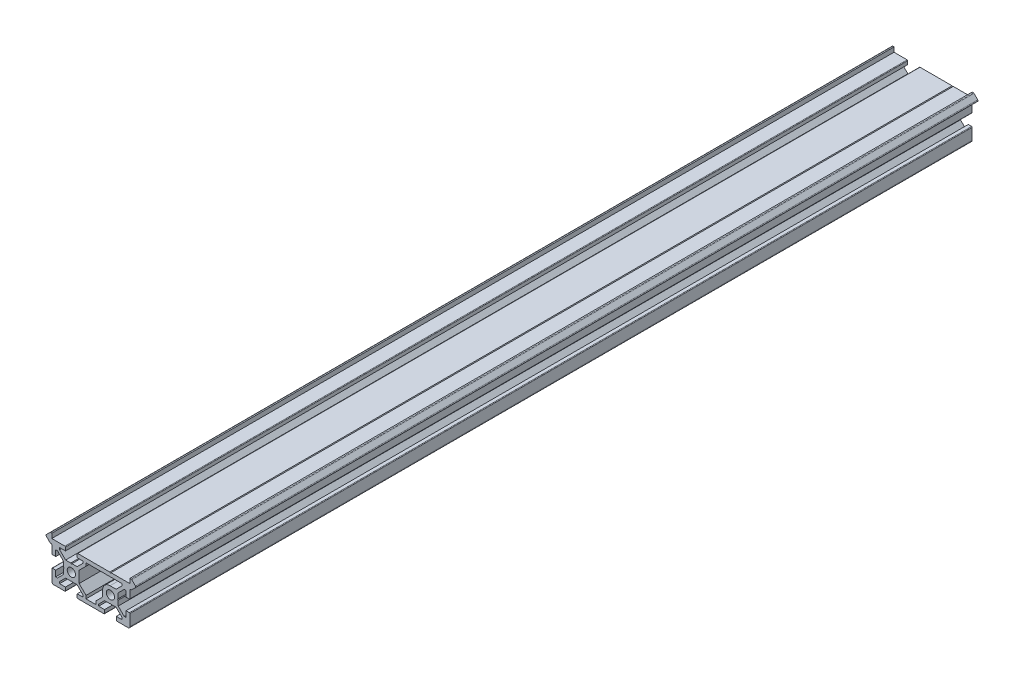
SolidWorks part; units mm, degrees
ref_plane "Front Plane" through (0, 0, 0) normal (0, 0, 1) x (1, 0, 0)
ref_plane "Top Plane" through (0, 0, 0) normal (0, 1, 0) x (1, 0, 0)
ref_plane "Right Plane" through (0, 0, 0) normal (1, 0, 0) x (0, 0, -1)
sketch "Model" plane through (0, 0, 0) normal (0, 0, 1) x (1, 0, 0)
  line L0 (0, 0) -> (0, 76.2) construction
  line L1 (0, 0) -> (101.6, 0) construction
  line L2 (0, 76.2) -> (101.6, 76.2) construction
  line L3 (101.6, 0) -> (101.6, 76.2) construction
  line L4 (28.7715, 48.1056) -> (30.6465, 49.9806)
  line L5 (31.5929, 50.127) -> (31.5929, 47.752)
  line L6 (31.5929, 44.877) -> (31.5929, 41.052)
  line L7 (31.5929, 34.452) -> (31.5929, 28.752)
  line L8 (33.5929, 31.752) -> (33.5929, 34.752)
  line L9 (33.5929, 40.752) -> (33.5929, 43.752)
  line L10 (35.5929, 29.752) -> (35.5929, 30.6914)
  line L11 (35.5929, 44.8127) -> (35.5929, 45.752)
  line L12 (37.5929, 40.6914) -> (37.5929, 38.052)
  line L13 (37.5929, 37.452) -> (37.5929, 34.8127)
  line L14 (38.5929, 28.052) -> (38.5929, 29.752)
  line L15 (38.5929, 45.752) -> (38.5929, 47.452)
  line L16 (32.5929, 27.752) -> (38.2929, 27.752)
  line L17 (44.8929, 27.752) -> (58.2929, 27.752)
  line L18 (64.8929, 27.752) -> (70.5929, 27.752)
  line L19 (37.5929, 38.052) -> (37.8929, 37.752)
  line L20 (41.5929, 34.052) -> (41.8929, 33.752)
  line L21 (30.6465, 45.5235) -> (28.7715, 47.3985)
  line L22 (41.8929, 41.752) -> (41.5929, 41.452)
  line L23 (37.8929, 37.752) -> (37.5929, 37.452)
  line L24 (67.5929, 29.752) -> (64.5929, 29.752)
  line L25 (58.5929, 29.752) -> (55.5929, 29.752)
  line L26 (54.0929, 29.752) -> (49.0929, 29.752)
  line L27 (47.5929, 29.752) -> (44.5929, 29.752)
  line L28 (38.5929, 29.752) -> (35.5929, 29.752)
  line L29 (34.5323, 43.752) -> (37.5929, 40.6914)
  line L30 (44.5323, 33.752) -> (47.5929, 30.6914)
  line L31 (44.5929, 47.452) -> (44.5929, 45.752)
  line L32 (44.5929, 29.752) -> (44.5929, 28.052)
  line L33 (47.5929, 44.8127) -> (44.5323, 41.752)
  line L34 (37.5929, 34.8127) -> (34.5323, 31.752)
  line L35 (69.5929, 31.752) -> (68.6536, 31.752)
  line L36 (34.5323, 31.752) -> (33.5929, 31.752)
  line L37 (49.0929, 31.3127) -> (45.5929, 34.8127)
  line L38 (38.6536, 41.752) -> (35.5929, 44.8127)
  line L39 (45.5929, 34.8127) -> (45.5929, 40.6914)
  line L40 (35.5929, 30.6914) -> (38.6536, 33.752)
  line L41 (45.5929, 40.6914) -> (49.0929, 44.1914)
  line L42 (38.6536, 33.752) -> (41.2929, 33.752)
  line L43 (41.8929, 33.752) -> (44.5323, 33.752)
  line L44 (58.6536, 33.752) -> (61.2929, 33.752)
  line L45 (61.8929, 33.752) -> (64.5323, 33.752)
  line L46 (41.5929, 41.452) -> (41.2929, 41.752)
  line L47 (47.5929, 45.752) -> (47.5929, 44.8127)
  line L48 (47.5929, 30.6914) -> (47.5929, 29.752)
  line L49 (41.2929, 33.752) -> (41.5929, 34.052)
  line L50 (71.2929, 34.752) -> (69.5929, 34.752)
  line L51 (33.5929, 34.752) -> (31.8929, 34.752)
  line L52 (49.0929, 29.752) -> (49.0929, 31.3127)
  line L53 (49.0929, 44.1914) -> (49.0929, 45.752)
  line L54 (61.5929, 47.452) -> (61.8929, 47.752)
  line L55 (31.8929, 40.752) -> (33.5929, 40.752)
  line L56 (69.5929, 40.752) -> (71.2929, 40.752)
  line L57 (54.0929, 31.3127) -> (54.0929, 29.752)
  line L58 (64.5323, 41.752) -> (61.4029, 41.752)
  line L59 (44.5323, 41.752) -> (41.8929, 41.752)
  line L60 (41.2929, 41.752) -> (38.6536, 41.752)
  line L61 (61.5929, 34.052) -> (61.8929, 33.752)
  line L62 (55.5929, 29.752) -> (55.5929, 30.6914)
  line L63 (33.5929, 43.752) -> (34.5323, 43.752)
  line L64 (68.6536, 43.752) -> (69.5929, 43.752)
  line L65 (57.5929, 37.942) -> (57.5929, 34.8127)
  line L66 (58.5929, 28.052) -> (58.5929, 29.752)
  line L67 (31.0929, 45.377) -> (31, 45.377)
  line L68 (72.0929, 45.377) -> (72.1858, 45.377)
  line L69 (35.5929, 45.752) -> (38.5929, 45.752)
  line L70 (44.5929, 45.752) -> (47.5929, 45.752)
  line L71 (49.0929, 45.752) -> (67.5929, 45.752)
  line L72 (64.5323, 33.752) -> (67.5929, 30.6914)
  line L73 (68.6536, 31.752) -> (65.5929, 34.8127)
  line L74 (67.5929, 44.8127) -> (64.5323, 41.752)
  line L75 (57.5929, 34.8127) -> (54.0929, 31.3127)
  line L76 (55.5929, 30.6914) -> (58.6536, 33.752)
  line L77 (65.5929, 40.6914) -> (68.6536, 43.752)
  line L78 (72.5394, 45.5235) -> (74.4144, 47.3985)
  line L79 (71.5929, 47.752) -> (61.8929, 47.752)
  line L80 (61.2929, 47.752) -> (44.8929, 47.752)
  line L81 (38.2929, 47.752) -> (31.5929, 47.752)
  line L82 (65.5929, 37.452) -> (65.2929, 37.752)
  line L83 (61.2929, 33.752) -> (61.5929, 34.052)
  line L84 (65.2929, 37.752) -> (65.5929, 38.052)
  line L85 (72.1858, 50.127) -> (71.5929, 50.127)
  line L86 (31, 50.127) -> (31.5929, 50.127)
  line L87 (64.5929, 29.752) -> (64.5929, 28.052)
  line L88 (61.2929, 47.752) -> (61.5929, 47.452)
  line L89 (65.5929, 34.8127) -> (65.5929, 37.452)
  line L90 (65.5929, 38.052) -> (65.5929, 40.6914)
  line L91 (67.5929, 45.752) -> (67.5929, 44.8127)
  line L92 (67.5929, 30.6914) -> (67.5929, 29.752)
  line L93 (69.5929, 43.752) -> (69.5929, 40.752)
  line L94 (69.5929, 34.752) -> (69.5929, 31.752)
  line L95 (71.5929, 50.127) -> (71.5929, 47.752)
  line L96 (71.5929, 28.752) -> (71.5929, 34.452)
  line L97 (71.5929, 41.052) -> (71.5929, 44.877)
  line L98 (74.4144, 48.1056) -> (72.5394, 49.9806)
  arc A0 (61.4029, 41.752) -> (57.5929, 37.942) centre (61.4029, 37.942) ccw
  circle A1 centre (61.5929, 37.752) radius 2.1
  circle A2 centre (41.5929, 37.752) radius 2.1
  arc A3 (31.5929, 28.752) -> (32.5929, 27.752) centre (32.5929, 28.752) ccw
  arc A4 (70.5929, 27.752) -> (71.5929, 28.752) centre (70.5929, 28.752) ccw
  arc A5 (31.5929, 44.877) -> (31.0929, 45.377) centre (31.0929, 44.877) ccw
  arc A6 (72.0929, 45.377) -> (71.5929, 44.877) centre (72.0929, 44.877) ccw
  arc A7 (31, 50.127) -> (30.6465, 49.9806) centre (31, 49.627) ccw
  arc A8 (28.7715, 48.1056) -> (28.7715, 47.3985) centre (29.125, 47.752) ccw
  arc A9 (30.6465, 45.5235) -> (31, 45.377) centre (31, 45.877) ccw
  arc A10 (72.5394, 49.9806) -> (72.1858, 50.127) centre (72.1858, 49.627) ccw
  arc A11 (74.4144, 47.3985) -> (74.4144, 48.1056) centre (74.0608, 47.752) ccw
  arc A12 (72.1858, 45.377) -> (72.5394, 45.5235) centre (72.1858, 45.877) ccw
  arc A13 (31.8929, 34.752) -> (31.5929, 34.452) centre (31.8929, 34.452) ccw
  arc A14 (44.8929, 47.752) -> (44.5929, 47.452) centre (44.8929, 47.452) ccw
  arc A15 (38.5929, 47.452) -> (38.2929, 47.752) centre (38.2929, 47.452) ccw
  arc A16 (31.5929, 41.052) -> (31.8929, 40.752) centre (31.8929, 41.052) ccw
  arc A17 (38.2929, 27.752) -> (38.5929, 28.052) centre (38.2929, 28.052) ccw
  arc A18 (44.5929, 28.052) -> (44.8929, 27.752) centre (44.8929, 28.052) ccw
  arc A19 (58.2929, 27.752) -> (58.5929, 28.052) centre (58.2929, 28.052) ccw
  arc A20 (64.5929, 28.052) -> (64.8929, 27.752) centre (64.8929, 28.052) ccw
  arc A21 (71.5929, 34.452) -> (71.2929, 34.752) centre (71.2929, 34.452) ccw
  arc A22 (71.2929, 40.752) -> (71.5929, 41.052) centre (71.2929, 41.052) ccw
extrude "Boss-Extrude1" add sketch "Model" against normal blind 431.1
ref_plane "Plane1" through (51.5929, 0, 0) normal (-1, 0, 0) x (0, 0, 1)
